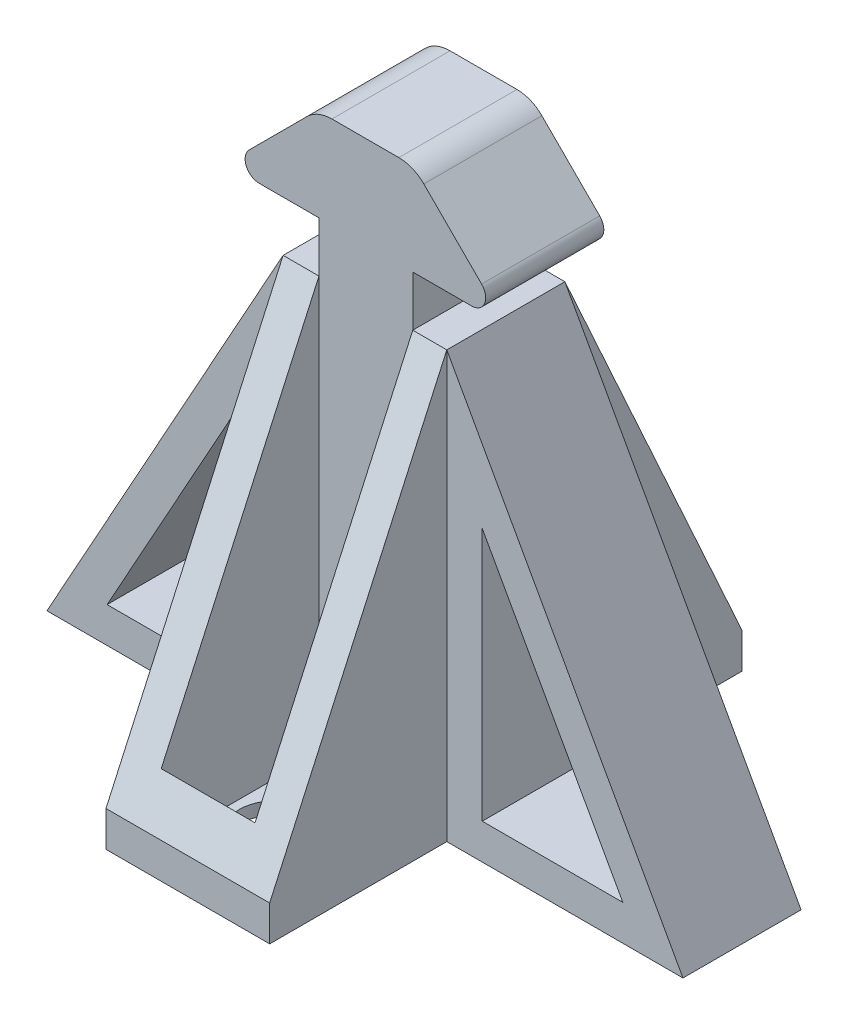
SolidWorks part; units mm, degrees
ref_plane "Front Plane" through (0, 0, 0) normal (0, 0, 1) x (1, 0, 0)
ref_plane "Top Plane" through (0, 0, 0) normal (0, 1, 0) x (1, 0, 0)
ref_plane "Right Plane" through (0, 0, 0) normal (1, 0, 0) x (0, 0, -1)
sketch "Sketch1" plane through (0, 0, 0) normal (0, 0, 1) x (1, 0, 0)
  line L0 (-113.4697, 674.107) -> (-113.4697, 674.0019) construction
  line L1 (-113.4697, 674.0019) -> (-110.4328, 674.0019) construction
  line L2 (-102.4905, 678.271) -> (-97.5028, 678.271)
  line L3 (-113.4697, 674.0019) -> (-110.4328, 674.0019)
  line L4 (-113.4697, 674.0019) -> (-113.4697, 640.5765)
  line L6 (-99.6065, 674.0019) -> (-99.6065, 637.935)
  line L7 (-111.1889, 637.935) -> (-111.1305, 637.935)
  line L8 (-112.2903, 678.271) -> (-110.4328, 678.271)
  line L11 (-110.4328, 678.271) -> (-110.4328, 674.0019)
  line L12 (-111.4436, 685.1974) -> (-116.3373, 680.3036)
  line L13 (-115.4954, 678.271) -> (-112.2903, 678.271)
  line L14 (-96.6608, 680.3036) -> (-101.5546, 685.1974)
  line L15 (-103.6661, 686.072) -> (-109.3321, 686.072)
  line L17 (-102.4905, 678.271) -> (-102.4905, 674.0019)
  line L19 (-102.4905, 674.0019) -> (-99.6065, 674.0019)
  line L20 (-99.6065, 637.935) -> (-113.4697, 637.935)
  line L21 (-111.1889, 637.935) -> (-111.1305, 637.935)
  line L22 (-99.6065, 640.5765) -> (-99.6065, 637.935)
  line L23 (-113.4697, 637.935) -> (-113.4697, 640.5765)
  line L26 (-111.1889, 637.935) -> (-111.1305, 637.935)
  line L27 (-99.6065, 640.5765) -> (-99.6065, 637.935)
  arc A12 (-109.3321, 686.072) -> (-111.4436, 685.1974) centre (-109.3321, 683.0859) ccw
  arc A13 (-116.3373, 680.3036) -> (-115.4954, 678.271) centre (-115.4954, 679.4617) ccw
  arc A14 (-97.5028, 678.271) -> (-96.6608, 680.3036) centre (-97.5028, 679.4617) ccw
  arc A15 (-101.5546, 685.1974) -> (-103.6661, 686.072) centre (-103.6661, 683.0859) ccw
extrude "Boss-Extrude1" add sketch "Sketch1" against normal blind 10 contours L6 L19 L17 L2 A14 L14 A15 L15 A12 L12 A13 L13 L8 L11 L3 L4 L23 L20
sketch "Sketch2" plane through (0, 0, 0) normal (0, 0, 1) x (1, 0, 0)
  line L0 (-113.4697, 674.0019) -> (-113.4697, 637.935) construction
  line L1 (-113.4697, 637.935) -> (-99.6065, 637.935)
  line L2 (-113.4697, 637.935) -> (-113.4697, 640.5756)
  line L3 (-113.4697, 640.5756) -> (-99.6065, 640.5756)
  line L4 (-99.6065, 637.935) -> (-99.6065, 640.5756)
  line L5 (-99.6065, 674.0019) -> (-99.6065, 637.935) construction
  dimension "D1" = 2.6406
extrude "Boss-Extrude2" add sketch "Sketch2" along normal blind 15 and the other way blind 25
sketch "Sketch3" plane through (0, 640.5756, 0) normal (0, 1, 0) x (1, 0, 0)
  line L0 (-106.5381, -15) -> (-106.4991, 0) construction
  line L1 (-99.6065, -15) -> (-113.4697, -15) construction
  line L2 (-103.6661, 0) -> (-109.3321, 0) construction
  line L3 (-99.6065, -7.5) -> (-113.4697, -7.5) construction
  line L4 (-99.6065, -15) -> (-99.6065, 0) construction
  line L5 (-113.4697, -15) -> (-113.4697, 0) construction
  circle A0 centre (-106.5381, -7.5) radius 3.15
extrude "Cut-Extrude1" cut sketch "Sketch3" against normal blind 2.65
sketch "Sketch4" plane through (0, 0, -10) normal (0, 0, -1) x (-1, 0, 0)
  line L0 (99.6065, 637.935) -> (79.6065, 637.935)
  line L1 (79.6065, 637.935) -> (99.6065, 674.0019)
  line L2 (99.6065, 674.0019) -> (99.6065, 637.935)
  line L3 (84.7005, 640.935) -> (96.6065, 662.4057)
  line L4 (96.6065, 662.4057) -> (96.6065, 640.935)
  line L5 (96.6065, 640.935) -> (84.7005, 640.935)
  line L6 (113.4697, 637.935) -> (133.4697, 637.935)
  line L7 (133.4697, 637.935) -> (113.4697, 674.0019)
  line L8 (113.4697, 674.0019) -> (113.4697, 637.935)
  line L9 (116.4697, 662.4057) -> (116.4697, 640.935)
  line L10 (116.4697, 640.935) -> (128.3758, 640.935)
  line L11 (128.3758, 640.935) -> (116.4697, 662.4057)
  dimension "D1" = 41.241
  dimension "D3" = 41.241
  dimension "D2" = 3
  dimension "D4" = 3
extrude "Boss-Extrude3" add sketch "Sketch4" against normal blind 10 contours L5 L4 L3 | L10 L11 L9 | L1 L2 L0 | L7 L8 L6
sketch "Sketch5" plane through (0, 640.5756, 0) normal (0, 1, 0) x (1, 0, 0)
  line L0 (-106.5381, 25) -> (-106.5381, 10) construction
  line L1 (-99.6065, 25) -> (-113.4697, 25) construction
  line L2 (-99.6065, 10) -> (-113.4697, 10) construction
  line L3 (-106.5381, 10) -> (-113.4697, 17.5) construction
  line L4 (-113.4697, 25) -> (-113.4697, 10) construction
  line L5 (-113.4697, 17.5) -> (-99.6065, 17.5) construction
  line L6 (-99.6065, 25) -> (-99.6065, 10) construction
  circle A0 centre (-106.5381, 17.5) radius 3.15
extrude "Cut-Extrude2" cut sketch "Sketch5" against normal blind 10 contours A0
sketch "Sketch7" plane through (0, 0, -10) normal (0, 0, -1) x (-1, 0, 0)
  line L1 (99.6065, 640.5756) -> (113.4697, 640.5756)
  line L2 (99.6065, 640.5756) -> (99.6065, 674.0019)
  line L3 (99.6065, 674.0019) -> (113.4697, 674.0019)
  line L4 (113.4697, 640.5756) -> (113.4697, 674.0019)
extrude "Boss-Extrude4" add sketch "Sketch7" along normal blind 15 and the other way blind 25
sketch "Sketch10" plane through (-99.6065, 0, 0) normal (1, 0, 0) x (0, 0, -1)
  line L0 (-15, 637.935) -> (-15, 640.935) construction
  line L1 (-15, 637.935) -> (-15, 674.0019) construction
  line L2 (-15, 640.935) -> (25, 640.935) construction
  line L3 (25, 637.935) -> (25, 674.0019) construction
  line L4 (-15, 640.935) -> (0, 674.0019)
  line L5 (0, 674.0019) -> (-15, 674.0019)
  line L6 (-15, 674.0019) -> (-15, 640.935)
  line L7 (25, 640.935) -> (25, 674.0019)
  line L8 (25, 674.0019) -> (10, 674.0019)
  line L9 (10, 674.0019) -> (25, 640.935)
extrude "Cut-Extrude3" cut sketch "Sketch10" against normal blind 15 contours L8 L9 L7 | L4 L5 L6
sketch "Sketch13" plane through (0, 674.0019, 0) normal (0, 1, 0) x (1, 0, 0)
  line L0 (-110.4328, 10) -> (-102.4905, 10) construction
  line L2 (-110.4328, 10) -> (-102.4905, 10)
  line L3 (-110.4328, 10) -> (-110.4328, 23.0798)
  line L4 (-110.4328, 23.0798) -> (-102.4905, 23.0798)
  line L5 (-102.4905, 10) -> (-102.4905, 23.0798)
  line L6 (-110.4328, 0) -> (-102.4905, 0)
  line L7 (-110.4328, 0) -> (-110.4328, -13.3584)
  line L8 (-110.4328, -13.3584) -> (-102.4905, -13.3584)
  line L9 (-102.4905, 0) -> (-102.4905, -13.3584)
extrude "Cut-Extrude4" cut sketch "Sketch13" against normal blind 35 contours L9 L6 L7 L8 | L4 L5 L2 L3
